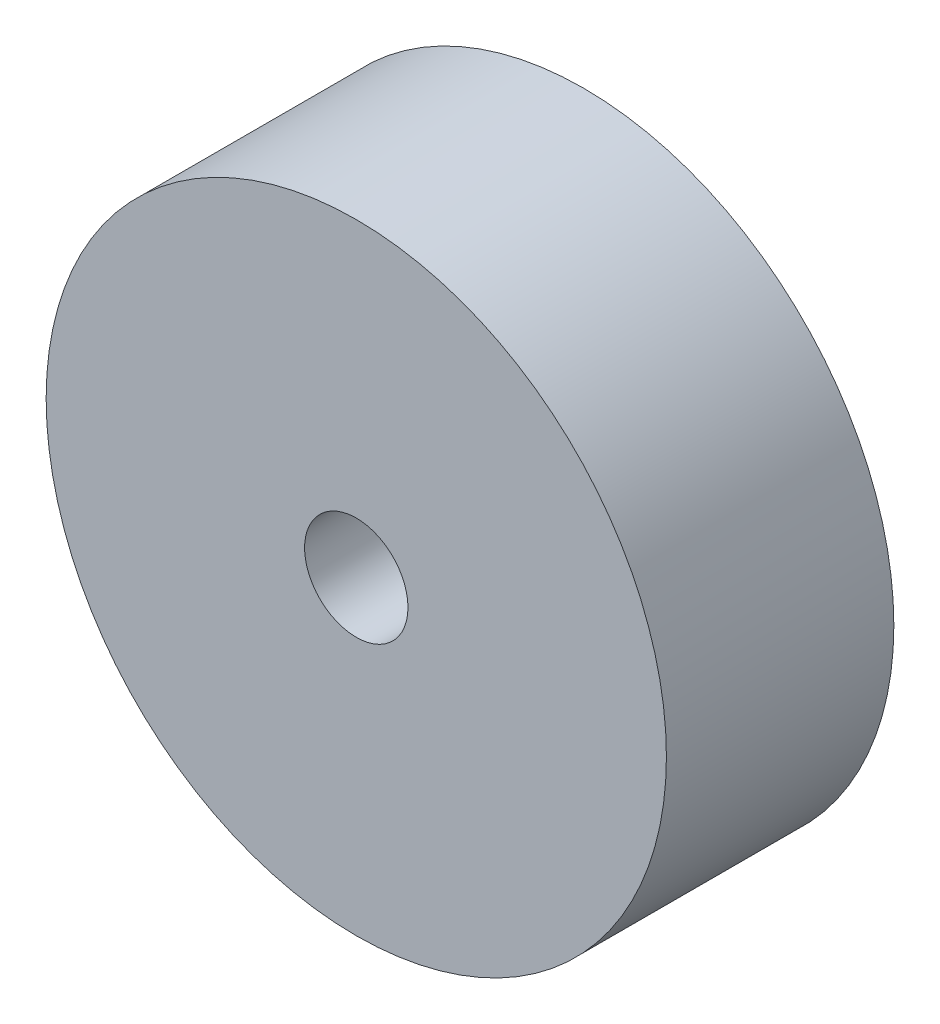
SolidWorks part; units mm, degrees
material "自訂玻璃纖維"
ref_plane "前基準面" through (0, 0, 0) normal (0, 0, 1) x (1, 0, 0)
ref_plane "上基準面" through (0, 0, 0) normal (0, 1, 0) x (1, 0, 0)
ref_plane "右基準面" through (0, 0, 0) normal (1, 0, 0) x (0, 0, -1)
sketch "草圖1" plane through (0, 0, 0) normal (0, 0, 1) x (1, 0, 0)
  circle A0 centre (-13.9029, 4.6452) radius 7.5
  circle A1 centre (-13.9029, 4.6452) radius 1.25
  point P13 (-13.9029, 4.6452)
  dimension "D1" = 15
  dimension "D2" = 2.5
extrude "填料-伸長1" add sketch "草圖1" along normal blind 5.5
